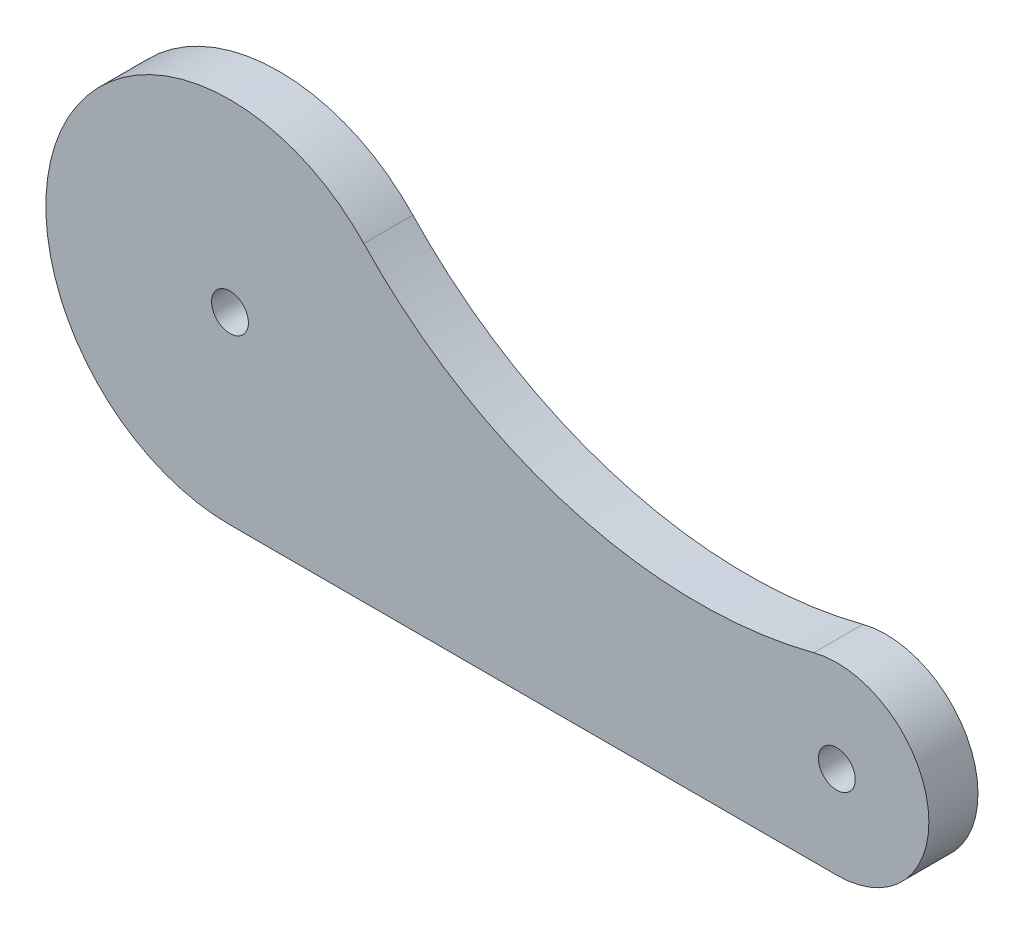
SolidWorks part; units mm, degrees
material "Acrílico (Impacto medio-alto)"
ref_plane "Piano frontale" through (0, 0, 0) normal (0, 0, 1) x (1, 0, 0)
ref_plane "Piano superiore" through (0, 0, 0) normal (0, 1, 0) x (1, 0, 0)
ref_plane "Piano destro" through (0, 0, 0) normal (1, 0, 0) x (0, 0, -1)
sketch "Schizzo1" plane through (0, 0, 0) normal (0, 0, 1) x (1, 0, 0)
  line L0 (0, -15) -> (49.4343, -15)
  circle A0 centre (0, 0) radius 1.5
  circle A1 centre (49.4343, -7.5) radius 1.5
  arc A2 (10.901, 10.3038) -> (0, -15) centre (0, 0) ccw
  arc A3 (49.4343, -15) -> (47.5542, -0.2395) centre (49.4343, -7.5) ccw
  arc A4 (10.901, 10.3038) -> (47.5542, -0.2395) centre (38.1536, 36.0631) ccw
  dimension "D1" = 3
  dimension "D2" = 3
  dimension "D4" = 30
  dimension "D5" = 15
  dimension "D6" = 75
  dimension "D3" = 50
extrude "Estrusione-Estrusione1" add sketch "Schizzo1" along normal blind 4
